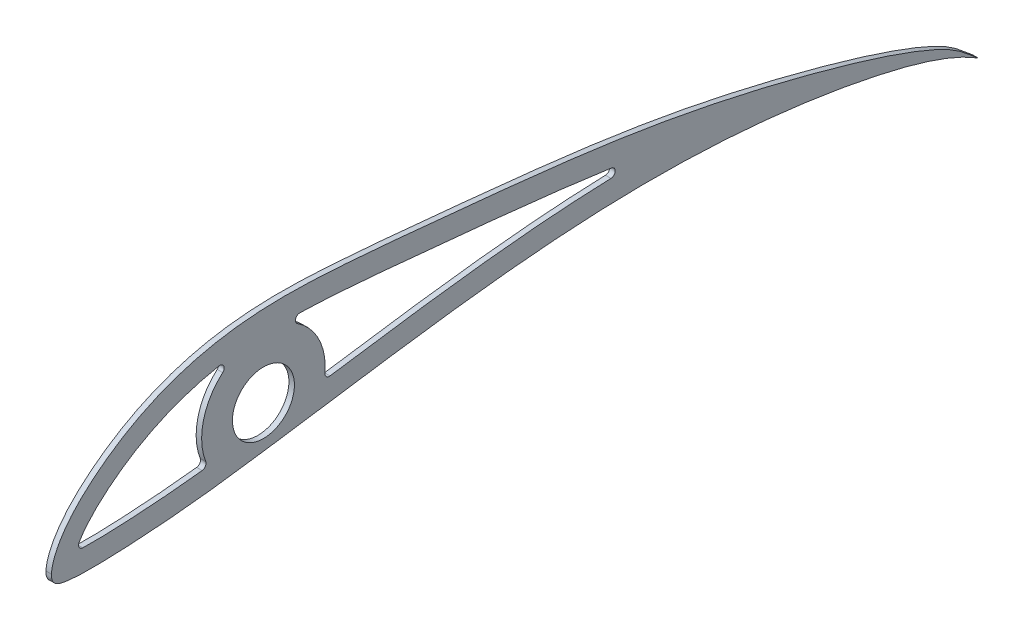
SolidWorks part; units mm, degrees
material "CARBON FIBERR"
ref_plane "Front Plane" through (0, 0, 0) normal (0, 0, 1) x (1, 0, 0)
ref_plane "Top Plane" through (0, 0, 0) normal (0, 1, 0) x (1, 0, 0)
ref_plane "Right Plane" through (0, 0, 0) normal (1, 0, 0) x (0, 0, -1)
ref_plane "Plane1" through (374.396, 0, 0) normal (1, 0, 0) x (0, 0, -1)
sketch "Sketch1" plane through (374.396, 0, 0) normal (1, 0, 0) x (0, 0, -1)
  spline S0 degree 3 poles (-1757.7941, -29.319) (301.3619, 37.93) (237.4166, 16.0959) (241.6902, -3.5548) (242.7876, -5.2858) (244.5591, -6.4782) (246.6935, -7.2344) (249.131, -7.7493) (251.9053, -8.1096) (255.0978, -8.3654) (258.8342, -8.5393) (263.2977, -8.6228) (268.7514, -8.5985) (275.555, -8.4304) (284.1155, -8.069) (294.702, -7.4673) (307.2387, -6.5655) (321.3512, -5.2677) (336.6352, -3.4986) (352.8428, -1.3174) (369.8087, 1.1216) (387.3069, 3.7048) (405.0531, 6.3509) (422.7994, 8.9824) (440.3769, 11.53) (457.7079, 13.943) (474.7726, 16.1729) (491.5765, 18.1853) (508.1369, 19.9445) (524.4805, 21.4229) (540.634, 22.6007) (556.6259, 23.457) (572.4794, 23.9812) (588.218, 24.1589) (603.8592, 23.9828) (619.4184, 23.4456) (634.8979, 22.5455) (650.289, 21.2804) (665.5566, 19.6555) (680.6274, 17.677) (695.3633, 15.3749) (709.5387, 12.7829) (722.8509, 9.9708) (734.984, 7.0126) (745.7106, 3.9665) (754.9656, 0.8711) (762.813, -2.2676) (829.3048, -33.2004) (850.9157, -142.8336) (1880.4183, 1654.1155) knots -0.098685 -0.098685 -0.098685 -0.098685 0.002957 0.006514 0.010125 0.013912 0.018 0.022509 0.02757 0.033355 0.040094 0.048109 0.05787 0.070043 0.085482 0.104923 0.128275 0.154506 0.182747 0.212766 0.244316 0.276878 0.309905 0.342853 0.375404 0.407446 0.438949 0.469916 0.500388 0.530405 0.560035 0.58933 0.61835 0.647141 0.675763 0.704248 0.732633 0.760909 0.78905 0.816946 0.844378 0.870951 0.896076 0.91909 0.939522 0.957298 0.972656 0.985921 1.359606 1.359606 1.359606 1.359606 only from (241.3, 0) to (776.3965, -9.3401) construction
  spline S1 degree 3 poles (-308.0702, -1684.8974) (911.1111, -68.0667) (826.2627, -53.3411) (768.0238, -2.1794) (762.2183, 1.8486) (755.2432, 5.6003) (746.9128, 9.3355) (737.0183, 13.2386) (725.4787, 17.3162) (712.4284, 21.5116) (698.1677, 25.7421) (683.0626, 29.924) (667.4447, 33.9819) (651.5631, 37.8588) (635.5717, 41.5076) (619.5421, 44.8962) (603.4804, 48.0063) (587.348, 50.8385) (571.0793, 53.4037) (554.5973, 55.7298) (537.8317, 57.8519) (520.7417, 59.8204) (503.3402, 61.6856) (485.7107, 63.4899) (468.0112, 65.2499) (450.4595, 66.9518) (433.3115, 68.5379) (416.8415, 69.9289) (401.2965, 71.0328) (386.8087, 71.7296) (373.3513, 71.8938) (360.7833, 71.4603) (348.942, 70.4185) (337.7011, 68.7634) (326.9806, 66.4985) (316.7399, 63.6365) (306.9731, 60.2063) (297.7138, 56.2454) (289.0297, 51.8366) (281.0253, 47.1113) (273.817, 42.2564) (267.5024, 37.4676) (262.1111, 32.912) (257.6099, 28.6711) (253.9113, 24.7595) (250.9022, 21.1572) (248.4636, 17.8395) (246.4919, 14.7802) (244.9074, 11.9506) (243.6495, 9.3232) (242.6798, 6.8706) (241.9668, 4.5716) (241.4951, 2.4096) (239.9127, -11.6076) (257.7656, -25.5664) (-1757.6087, 31.8282) knots -0.372812 -0.372812 -0.372812 -0.372812 0.007664 0.018831 0.030906 0.044389 0.060047 0.078461 0.099805 0.123817 0.149891 0.177318 0.205492 0.23398 0.26251 0.290968 0.319358 0.347763 0.376321 0.405183 0.434504 0.464387 0.494832 0.525708 0.55674 0.587526 0.617605 0.646485 0.67366 0.698816 0.722063 0.743776 0.764323 0.783978 0.802952 0.821386 0.839352 0.856859 0.873831 0.890071 0.905268 0.919096 0.931351 0.942034 0.951308 0.959388 0.966479 0.972752 0.978344 0.983369 0.987921 0.992076 0.995899 0.999439 1.065368 1.065368 1.065368 1.065368 only from (776.3965, -9.3401) to (241.3, 0) construction
  spline S2 degree 3 poles (241.3, 0) (241.2977, -0.539) (241.2925, -1.7262) (241.6902, -3.5548) (242.7876, -5.2858) (244.5591, -6.4782) (246.6935, -7.2344) (249.131, -7.7493) (251.9053, -8.1096) (255.0978, -8.3654) (258.8342, -8.5393) (263.2977, -8.6228) (268.7514, -8.5985) (275.555, -8.4304) (284.1155, -8.069) (294.702, -7.4673) (307.2387, -6.5655) (321.3512, -5.2677) (336.6352, -3.4986) (352.8428, -1.3174) (369.8087, 1.1216) (387.3069, 3.7048) (405.0531, 6.3509) (422.7994, 8.9824) (440.3769, 11.53) (457.7079, 13.943) (474.7726, 16.1729) (491.5765, 18.1853) (508.1369, 19.9445) (524.4805, 21.4229) (540.634, 22.6007) (556.6259, 23.457) (572.4794, 23.9812) (588.218, 24.1589) (603.8592, 23.9828) (619.4184, 23.4456) (634.8979, 22.5455) (650.289, 21.2804) (665.5566, 19.6555) (680.6274, 17.677) (695.3633, 15.3749) (709.5387, 12.7829) (722.8509, 9.9708) (734.984, 7.0126) (745.7106, 3.9665) (754.9656, 0.8711) (762.813, -2.2676) (769.8706, -5.5509) (774.1784, -8.0522) (776.3965, -9.3401) knots 0 0 0 0 0.002957 0.006514 0.010125 0.013912 0.018 0.022509 0.02757 0.033355 0.040094 0.048109 0.05787 0.070043 0.085482 0.104923 0.128275 0.154506 0.182747 0.212766 0.244316 0.276878 0.309905 0.342853 0.375404 0.407446 0.438949 0.469916 0.500388 0.530405 0.560035 0.58933 0.61835 0.647141 0.675763 0.704248 0.732633 0.760909 0.78905 0.816946 0.844378 0.870951 0.896076 0.91909 0.939522 0.957298 0.972656 0.985921 1 1 1 1
  spline S3 degree 3 poles (776.3965, -9.3401) (775.2642, -8.4018) (772.4822, -6.0961) (768.0238, -2.1794) (762.2183, 1.8486) (755.2432, 5.6003) (746.9128, 9.3355) (737.0183, 13.2386) (725.4787, 17.3162) (712.4284, 21.5116) (698.1677, 25.7421) (683.0626, 29.924) (667.4447, 33.9819) (651.5631, 37.8588) (635.5717, 41.5076) (619.5421, 44.8962) (603.4804, 48.0063) (587.348, 50.8385) (571.0793, 53.4037) (554.5973, 55.7298) (537.8317, 57.8519) (520.7417, 59.8204) (503.3402, 61.6856) (485.7107, 63.4899) (468.0112, 65.2499) (450.4595, 66.9518) (433.3115, 68.5379) (416.8415, 69.9289) (401.2965, 71.0328) (386.8087, 71.7296) (373.3513, 71.8938) (360.7833, 71.4603) (348.942, 70.4185) (337.7011, 68.7634) (326.9806, 66.4985) (316.7399, 63.6365) (306.9731, 60.2063) (297.7138, 56.2454) (289.0297, 51.8366) (281.0253, 47.1113) (273.817, 42.2564) (267.5024, 37.4676) (262.1111, 32.912) (257.6099, 28.6711) (253.9113, 24.7595) (250.9022, 21.1572) (248.4636, 17.8395) (246.4919, 14.7802) (244.9074, 11.9506) (243.6495, 9.3232) (242.6798, 6.8706) (241.9668, 4.5716) (241.4951, 2.4096) (241.324, 0.8942) (241.3029, 0.1075) (241.3, 0) knots 0 0 0 0 0.007664 0.018831 0.030906 0.044389 0.060047 0.078461 0.099805 0.123817 0.149891 0.177318 0.205492 0.23398 0.26251 0.290968 0.319358 0.347763 0.376321 0.405183 0.434504 0.464387 0.494832 0.525708 0.55674 0.587526 0.617605 0.646485 0.67366 0.698816 0.722063 0.743776 0.764323 0.783978 0.802952 0.821386 0.839352 0.856859 0.873831 0.890071 0.905268 0.919096 0.931351 0.942034 0.951308 0.959388 0.966479 0.972752 0.978344 0.983369 0.987921 0.992076 0.995899 0.999439 1 1 1 1
extrude "Boss-Extrude1" add sketch "Sketch1" along normal blind 3.175
sketch "Sketch2" plane through (377.571, 0, 0) normal (1, 0, 0) x (0, 0, -1)
  circle A0 centre (363.695, 24.544) radius 17.907 construction
  circle A1 centre (363.695, 24.544) radius 17.907
  circle A2 centre (363.695, 24.544) radius 35.687
  spline S2 degree 3 poles (-913.9077, -2480.4045) (935.2001, -71.4809) (834.1009, -60.2269) (768.0238, -2.1794) (762.2183, 1.8486) (755.2432, 5.6003) (746.9128, 9.3355) (737.0183, 13.2386) (725.4787, 17.3162) (712.4284, 21.5116) (698.1677, 25.7421) (683.0626, 29.924) (667.4447, 33.9819) (651.5631, 37.8588) (635.5717, 41.5076) (619.5421, 44.8962) (603.4804, 48.0063) (587.348, 50.8385) (571.0793, 53.4037) (554.5973, 55.7298) (537.8317, 57.8519) (520.7417, 59.8204) (503.3402, 61.6856) (485.7107, 63.4899) (468.0112, 65.2499) (450.4595, 66.9518) (433.3115, 68.5379) (416.8415, 69.9289) (401.2965, 71.0328) (386.8087, 71.7296) (373.3513, 71.8938) (360.7833, 71.4603) (348.942, 70.4185) (337.7011, 68.7634) (326.9806, 66.4985) (316.7399, 63.6365) (306.9731, 60.2063) (297.7138, 56.2454) (289.0297, 51.8366) (281.0253, 47.1113) (273.817, 42.2564) (267.5024, 37.4676) (262.1111, 32.912) (257.6099, 28.6711) (253.9113, 24.7595) (250.9022, 21.1572) (248.4636, 17.8395) (246.4919, 14.7802) (244.9074, 11.9506) (243.6495, 9.3232) (242.6798, 6.8706) (241.9668, 4.5716) (241.4951, 2.4096) (239.7085, -13.416) (262.9843, -29.3789) (-2756.235, 61.0933) knots -0.427147 -0.427147 -0.427147 -0.427147 0.007664 0.018831 0.030906 0.044389 0.060047 0.078461 0.099805 0.123817 0.149891 0.177318 0.205492 0.23398 0.26251 0.290968 0.319358 0.347763 0.376321 0.405183 0.434504 0.464387 0.494832 0.525708 0.55674 0.587526 0.617605 0.646485 0.67366 0.698816 0.722063 0.743776 0.764323 0.783978 0.802952 0.821386 0.839352 0.856859 0.873831 0.890071 0.905268 0.919096 0.931351 0.942034 0.951308 0.959388 0.966479 0.972752 0.978344 0.983369 0.987921 0.992076 0.995899 0.999439 1.074824 1.074824 1.074824 1.074824 only from (776.3965, -9.3401) to (241.3, 0)
  spline S3 degree 3 poles (-2757.0722, -63.1376) (319.972, 43.9085) (236.8558, 18.6742) (241.6902, -3.5548) (242.7876, -5.2858) (244.5591, -6.4782) (246.6935, -7.2344) (249.131, -7.7493) (251.9053, -8.1096) (255.0978, -8.3654) (258.8342, -8.5393) (263.2977, -8.6228) (268.7514, -8.5985) (275.555, -8.4304) (284.1155, -8.069) (294.702, -7.4673) (307.2387, -6.5655) (321.3512, -5.2677) (336.6352, -3.4986) (352.8428, -1.3174) (369.8087, 1.1216) (387.3069, 3.7048) (405.0531, 6.3509) (422.7994, 8.9824) (440.3769, 11.53) (457.7079, 13.943) (474.7726, 16.1729) (491.5765, 18.1853) (508.1369, 19.9445) (524.4805, 21.4229) (540.634, 22.6007) (556.6259, 23.457) (572.4794, 23.9812) (588.218, 24.1589) (603.8592, 23.9828) (619.4184, 23.4456) (634.8979, 22.5455) (650.289, 21.2804) (665.5566, 19.6555) (680.6274, 17.677) (695.3633, 15.3749) (709.5387, 12.7829) (722.8509, 9.9708) (734.984, 7.0126) (745.7106, 3.9665) (754.9656, 0.8711) (762.813, -2.2676) (837.931, -37.2134) (855.9752, -173.8618) (2373.6724, 2523.7984) knots -0.112962 -0.112962 -0.112962 -0.112962 0.002957 0.006514 0.010125 0.013912 0.018 0.022509 0.02757 0.033355 0.040094 0.048109 0.05787 0.070043 0.085482 0.104923 0.128275 0.154506 0.182747 0.212766 0.244316 0.276878 0.309905 0.342853 0.375404 0.407446 0.438949 0.469916 0.500388 0.530405 0.560035 0.58933 0.61835 0.647141 0.675763 0.704248 0.732633 0.760909 0.78905 0.816946 0.844378 0.870951 0.896076 0.91909 0.939522 0.957298 0.972656 0.985921 1.411798 1.411798 1.411798 1.411798 only from (241.3, 0) to (776.3965, -9.3401)
  spline S4 degree 3 poles (776.3965, -9.3401) (775.2642, -8.4018) (772.4822, -6.0961) (768.0238, -2.1794) (762.2183, 1.8486) (755.2432, 5.6003) (746.9128, 9.3355) (737.0183, 13.2386) (725.4787, 17.3162) (712.4284, 21.5116) (698.1677, 25.7421) (683.0626, 29.924) (667.4447, 33.9819) (651.5631, 37.8588) (635.5717, 41.5076) (619.5421, 44.8962) (603.4804, 48.0063) (587.348, 50.8385) (571.0793, 53.4037) (554.5973, 55.7298) (537.8317, 57.8519) (520.7417, 59.8204) (503.3402, 61.6856) (485.7107, 63.4899) (468.0112, 65.2499) (450.4595, 66.9518) (433.3115, 68.5379) (416.8415, 69.9289) (401.2965, 71.0328) (386.8087, 71.7296) (373.3513, 71.8938) (360.7833, 71.4603) (348.942, 70.4185) (337.7011, 68.7634) (326.9806, 66.4985) (316.7399, 63.6365) (306.9731, 60.2063) (297.7138, 56.2454) (289.0297, 51.8366) (281.0253, 47.1113) (273.817, 42.2564) (267.5024, 37.4676) (262.1111, 32.912) (257.6099, 28.6711) (253.9113, 24.7595) (250.9022, 21.1572) (248.4636, 17.8395) (246.4919, 14.7802) (244.9074, 11.9506) (243.6495, 9.3232) (242.6798, 6.8706) (241.9668, 4.5716) (241.4951, 2.4096) (241.324, 0.8942) (241.3029, 0.1075) (241.3, 0) knots 0 0 0 0 0.007664 0.018831 0.030906 0.044389 0.060047 0.078461 0.099805 0.123817 0.149891 0.177318 0.205492 0.23398 0.26251 0.290968 0.319358 0.347763 0.376321 0.405183 0.434504 0.464387 0.494832 0.525708 0.55674 0.587526 0.617605 0.646485 0.67366 0.698816 0.722063 0.743776 0.764323 0.783978 0.802952 0.821386 0.839352 0.856859 0.873831 0.890071 0.905268 0.919096 0.931351 0.942034 0.951308 0.959388 0.966479 0.972752 0.978344 0.983369 0.987921 0.992076 0.995899 0.999439 1 1 1 1
  spline S5 degree 3 poles (241.3, 0) (241.2977, -0.539) (241.2925, -1.7262) (241.6902, -3.5548) (242.7876, -5.2858) (244.5591, -6.4782) (246.6935, -7.2344) (249.131, -7.7493) (251.9053, -8.1096) (255.0978, -8.3654) (258.8342, -8.5393) (263.2977, -8.6228) (268.7514, -8.5985) (275.555, -8.4304) (284.1155, -8.069) (294.702, -7.4673) (307.2387, -6.5655) (321.3512, -5.2677) (336.6352, -3.4986) (352.8428, -1.3174) (369.8087, 1.1216) (387.3069, 3.7048) (405.0531, 6.3509) (422.7994, 8.9824) (440.3769, 11.53) (457.7079, 13.943) (474.7726, 16.1729) (491.5765, 18.1853) (508.1369, 19.9445) (524.4805, 21.4229) (540.634, 22.6007) (556.6259, 23.457) (572.4794, 23.9812) (588.218, 24.1589) (603.8592, 23.9828) (619.4184, 23.4456) (634.8979, 22.5455) (650.289, 21.2804) (665.5566, 19.6555) (680.6274, 17.677) (695.3633, 15.3749) (709.5387, 12.7829) (722.8509, 9.9708) (734.984, 7.0126) (745.7106, 3.9665) (754.9656, 0.8711) (762.813, -2.2676) (769.8706, -5.5509) (774.1784, -8.0522) (776.3965, -9.3401) knots 0 0 0 0 0.002957 0.006514 0.010125 0.013912 0.018 0.022509 0.02757 0.033355 0.040094 0.048109 0.05787 0.070043 0.085482 0.104923 0.128275 0.154506 0.182747 0.212766 0.244316 0.276878 0.309905 0.342853 0.375404 0.407446 0.438949 0.469916 0.500388 0.530405 0.560035 0.58933 0.61835 0.647141 0.675763 0.704248 0.732633 0.760909 0.78905 0.816946 0.844378 0.870951 0.896076 0.91909 0.939522 0.957298 0.972656 0.985921 1 1 1 1
  spline S6 degree 1 poles (768.2925, -19.1184) (253.9954, -0.3405) knots 0 0 1 1 construction
  spline S7 degree 3 poles (768.2925, -19.1184) (767.7055, -18.6319) (766.5521, -17.6764) (764.7068, -16.1275) (762.9599, -14.626) (761.3891, -13.2951) (759.9883, -12.1658) (758.5753, -11.1145) (757.0969, -10.096) (755.0749, -8.8073) (752.3716, -7.271) (748.8095, -5.4786) (745.0866, -3.768) (739.9114, -1.5568) (733.2643, 1.0537) (725.0959, 3.9925) (716.7979, 6.7742) (705.6123, 10.3092) (691.4579, 14.4604) (674.3192, 19.1127) (657.0792, 23.4781) (634.005, 28.9244) (605.0355, 34.9818) (570.0445, 40.8892) (534.7626, 45.5364) (499.1768, 49.3866) (463.4209, 52.9571) (433.662, 55.8004) (409.9704, 57.7265) (386.4587, 59.2124) (363.5, 59.3322) (341.2009, 56.6472) (324.9291, 53.0252) (309.2507, 47.6699) (296.8532, 41.7283) (287.4017, 36.107) (280.5793, 31.4827) (274.0623, 26.4647) (267.9717, 21.1127) (263.4702, 16.4451) (260.3448, 12.5985) (258.2519, 9.6466) (256.7614, 7.1683) (255.7551, 5.2111) (255.1185, 3.7989) (254.6054, 2.4516) (254.2951, 1.4214) (254.1281, 0.7117) (254.0567, 0.3209) (254.0216, 0.0729) (254.0094, -0.0402) (254.0038, -0.1078) (254.0018, -0.1386) (254.0007, -0.1602) (254.0005, -0.165) (253.9988, -0.2142) (253.9964, -0.303) (253.9954, -0.3405) knots 0 0 0 0 0.003906 0.007812 0.011719 0.015625 0.019531 0.023437 0.027344 0.03125 0.039062 0.046875 0.054687 0.0625 0.078125 0.09375 0.109375 0.125 0.15625 0.1875 0.21875 0.25 0.3125 0.375 0.4375 0.5 0.5625 0.625 0.65625 0.6875 0.75 0.78125 0.8125 0.84375 0.875 0.890625 0.90625 0.921875 0.9375 0.953125 0.960937 0.96875 0.976562 0.980469 0.984375 0.988281 0.992187 0.994141 0.996094 0.99707 0.998047 0.998535 0.999023 0.999268 0.999512 0.999756 1 1 1 1
  spline S8 degree 3 poles (-2757.0722, -63.1376) (319.972, 43.9085) (236.8558, 18.6742) (241.6902, -3.5548) (242.7876, -5.2858) (244.5591, -6.4782) (246.6935, -7.2344) (249.131, -7.7493) (251.9053, -8.1096) (255.0978, -8.3654) (258.8342, -8.5393) (263.2977, -8.6228) (268.7514, -8.5985) (275.555, -8.4304) (284.1155, -8.069) (294.702, -7.4673) (307.2387, -6.5655) (321.3512, -5.2677) (336.6352, -3.4986) (352.8428, -1.3174) (369.8087, 1.1216) (387.3069, 3.7048) (405.0531, 6.3509) (422.7994, 8.9824) (440.3769, 11.53) (457.7079, 13.943) (474.7726, 16.1729) (491.5765, 18.1853) (508.1369, 19.9445) (524.4805, 21.4229) (540.634, 22.6007) (556.6259, 23.457) (572.4794, 23.9812) (588.218, 24.1589) (603.8592, 23.9828) (619.4184, 23.4456) (634.8979, 22.5455) (650.289, 21.2804) (665.5566, 19.6555) (680.6274, 17.677) (695.3633, 15.3749) (709.5387, 12.7829) (722.8509, 9.9708) (734.984, 7.0126) (745.7106, 3.9665) (754.9656, 0.8711) (762.813, -2.2676) (837.931, -37.2134) (855.9752, -173.8618) (2373.6724, 2523.7984) knots -0.112962 -0.112962 -0.112962 -0.112962 0.002957 0.006514 0.010125 0.013912 0.018 0.022509 0.02757 0.033355 0.040094 0.048109 0.05787 0.070043 0.085482 0.104923 0.128275 0.154506 0.182747 0.212766 0.244316 0.276878 0.309905 0.342853 0.375404 0.407446 0.438949 0.469916 0.500388 0.530405 0.560035 0.58933 0.61835 0.647141 0.675763 0.704248 0.732633 0.760909 0.78905 0.816946 0.844378 0.870951 0.896076 0.91909 0.939522 0.957298 0.972656 0.985921 1.411798 1.411798 1.411798 1.411798 only from (241.3, 0) to (776.3965, -9.3401)
  spline S9 degree 3 poles (-913.9077, -2480.4045) (935.2001, -71.4809) (834.1009, -60.2269) (768.0238, -2.1794) (762.2183, 1.8486) (755.2432, 5.6003) (746.9128, 9.3355) (737.0183, 13.2386) (725.4787, 17.3162) (712.4284, 21.5116) (698.1677, 25.7421) (683.0626, 29.924) (667.4447, 33.9819) (651.5631, 37.8588) (635.5717, 41.5076) (619.5421, 44.8962) (603.4804, 48.0063) (587.348, 50.8385) (571.0793, 53.4037) (554.5973, 55.7298) (537.8317, 57.8519) (520.7417, 59.8204) (503.3402, 61.6856) (485.7107, 63.4899) (468.0112, 65.2499) (450.4595, 66.9518) (433.3115, 68.5379) (416.8415, 69.9289) (401.2965, 71.0328) (386.8087, 71.7296) (373.3513, 71.8938) (360.7833, 71.4603) (348.942, 70.4185) (337.7011, 68.7634) (326.9806, 66.4985) (316.7399, 63.6365) (306.9731, 60.2063) (297.7138, 56.2454) (289.0297, 51.8366) (281.0253, 47.1113) (273.817, 42.2564) (267.5024, 37.4676) (262.1111, 32.912) (257.6099, 28.6711) (253.9113, 24.7595) (250.9022, 21.1572) (248.4636, 17.8395) (246.4919, 14.7802) (244.9074, 11.9506) (243.6495, 9.3232) (242.6798, 6.8706) (241.9668, 4.5716) (241.4951, 2.4096) (239.7085, -13.416) (262.9843, -29.3789) (-2756.235, 61.0933) knots -0.427147 -0.427147 -0.427147 -0.427147 0.007664 0.018831 0.030906 0.044389 0.060047 0.078461 0.099805 0.123817 0.149891 0.177318 0.205492 0.23398 0.26251 0.290968 0.319358 0.347763 0.376321 0.405183 0.434504 0.464387 0.494832 0.525708 0.55674 0.587526 0.617605 0.646485 0.67366 0.698816 0.722063 0.743776 0.764323 0.783978 0.802952 0.821386 0.839352 0.856859 0.873831 0.890071 0.905268 0.919096 0.931351 0.942034 0.951308 0.959388 0.966479 0.972752 0.978344 0.983369 0.987921 0.992076 0.995899 0.999439 1.074824 1.074824 1.074824 1.074824 only from (776.3965, -9.3401) to (241.3, 0)
  spline S10 degree 3 poles (241.3, 0) (241.2977, -0.539) (241.2925, -1.7262) (241.6902, -3.5548) (242.7876, -5.2858) (244.5591, -6.4782) (246.6935, -7.2344) (249.131, -7.7493) (251.9053, -8.1096) (255.0978, -8.3654) (258.8342, -8.5393) (263.2977, -8.6228) (268.7514, -8.5985) (275.555, -8.4304) (284.1155, -8.069) (294.702, -7.4673) (307.2387, -6.5655) (321.3512, -5.2677) (336.6352, -3.4986) (352.8428, -1.3174) (369.8087, 1.1216) (387.3069, 3.7048) (405.0531, 6.3509) (422.7994, 8.9824) (440.3769, 11.53) (457.7079, 13.943) (474.7726, 16.1729) (491.5765, 18.1853) (508.1369, 19.9445) (524.4805, 21.4229) (540.634, 22.6007) (556.6259, 23.457) (572.4794, 23.9812) (588.218, 24.1589) (603.8592, 23.9828) (619.4184, 23.4456) (634.8979, 22.5455) (650.289, 21.2804) (665.5566, 19.6555) (680.6274, 17.677) (695.3633, 15.3749) (709.5387, 12.7829) (722.8509, 9.9708) (734.984, 7.0126) (745.7106, 3.9665) (754.9656, 0.8711) (762.813, -2.2676) (769.8706, -5.5509) (774.1784, -8.0522) (776.3965, -9.3401) knots 0 0 0 0 0.002957 0.006514 0.010125 0.013912 0.018 0.022509 0.02757 0.033355 0.040094 0.048109 0.05787 0.070043 0.085482 0.104923 0.128275 0.154506 0.182747 0.212766 0.244316 0.276878 0.309905 0.342853 0.375404 0.407446 0.438949 0.469916 0.500388 0.530405 0.560035 0.58933 0.61835 0.647141 0.675763 0.704248 0.732633 0.760909 0.78905 0.816946 0.844378 0.870951 0.896076 0.91909 0.939522 0.957298 0.972656 0.985921 1 1 1 1
  spline S11 degree 3 poles (776.3965, -9.3401) (775.2642, -8.4018) (772.4822, -6.0961) (768.0238, -2.1794) (762.2183, 1.8486) (755.2432, 5.6003) (746.9128, 9.3355) (737.0183, 13.2386) (725.4787, 17.3162) (712.4284, 21.5116) (698.1677, 25.7421) (683.0626, 29.924) (667.4447, 33.9819) (651.5631, 37.8588) (635.5717, 41.5076) (619.5421, 44.8962) (603.4804, 48.0063) (587.348, 50.8385) (571.0793, 53.4037) (554.5973, 55.7298) (537.8317, 57.8519) (520.7417, 59.8204) (503.3402, 61.6856) (485.7107, 63.4899) (468.0112, 65.2499) (450.4595, 66.9518) (433.3115, 68.5379) (416.8415, 69.9289) (401.2965, 71.0328) (386.8087, 71.7296) (373.3513, 71.8938) (360.7833, 71.4603) (348.942, 70.4185) (337.7011, 68.7634) (326.9806, 66.4985) (316.7399, 63.6365) (306.9731, 60.2063) (297.7138, 56.2454) (289.0297, 51.8366) (281.0253, 47.1113) (273.817, 42.2564) (267.5024, 37.4676) (262.1111, 32.912) (257.6099, 28.6711) (253.9113, 24.7595) (250.9022, 21.1572) (248.4636, 17.8395) (246.4919, 14.7802) (244.9074, 11.9506) (243.6495, 9.3232) (242.6798, 6.8706) (241.9668, 4.5716) (241.4951, 2.4096) (241.324, 0.8942) (241.3029, 0.1075) (241.3, 0) knots 0 0 0 0 0.007664 0.018831 0.030906 0.044389 0.060047 0.078461 0.099805 0.123817 0.149891 0.177318 0.205492 0.23398 0.26251 0.290968 0.319358 0.347763 0.376321 0.405183 0.434504 0.464387 0.494832 0.525708 0.55674 0.587526 0.617605 0.646485 0.67366 0.698816 0.722063 0.743776 0.764323 0.783978 0.802952 0.821386 0.839352 0.856859 0.873831 0.890071 0.905268 0.919096 0.931351 0.942034 0.951308 0.959388 0.966479 0.972752 0.978344 0.983369 0.987921 0.992076 0.995899 0.999439 1 1 1 1
  spline S12 degree 1 poles (253.1556, 4.5534) (782.7736, 1.6427) knots 0 0 1 1 construction
  spline S13 degree 3 poles (253.1556, 4.5534) (253.7188, 4.4938) (254.8178, 4.3964) (257.2557, 4.2396) (260.3853, 4.1248) (264.2721, 4.0797) (269.5349, 4.1151) (276.222, 4.2993) (284.3357, 4.665) (292.4797, 5.1316) (303.3377, 5.8714) (316.8507, 7.0275) (333.0267, 8.8444) (349.2935, 11.0105) (365.6512, 13.3505) (387.5036, 16.5666) (414.8655, 20.666) (447.8248, 25.4588) (480.9692, 29.8294) (514.3423, 33.4345) (547.9337, 35.9294) (581.6886, 37.0356) (615.5185, 36.548) (649.3071, 34.3571) (677.3437, 31.0752) (699.6727, 27.5411) (716.3703, 24.3934) (733.0395, 20.6698) (746.9514, 16.9044) (756.7496, 13.6737) (762.3626, 11.583) (766.5394, 9.8938) (770.6824, 8.0838) (774.215, 6.3904) (777.0399, 4.9019) (779.0372, 3.7951) (780.9596, 2.6961) (782.1628, 1.9973) (782.7736, 1.6427) knots 0.027647 0.027647 0.027647 0.027647 0.031446 0.035244 0.04284 0.050437 0.058033 0.073227 0.08842 0.103613 0.118806 0.149192 0.179578 0.209964 0.24035 0.270736 0.331508 0.39228 0.453052 0.513824 0.574596 0.635368 0.69614 0.756912 0.817684 0.84807 0.878456 0.908842 0.939228 0.954421 0.962017 0.969614 0.97721 0.984807 0.988605 0.992403 0.996202 1 1 1 1
  dimension "D1" = 0
  dimension "D2" = 0
  dimension "D3" = 12.7
  dimension "D4" = 17.78
extrude "Cut-Extrude1" cut sketch "Sketch2" against normal through all contours A1 S13 | S13 A1 | S7 S13 A2 | A2 S13 S7
fillet "Fillet1" radius 2.54 6 edges at (375.9835, 36.7768, -593.9226) (375.9835, 4.3629, -255.3772) (375.9835, 18.2617, -398.8247) (375.9835, 8.7389, -331.6988) (375.9835, 59.0766, -372.6986) (375.9835, 57.7011, -350.4977)
